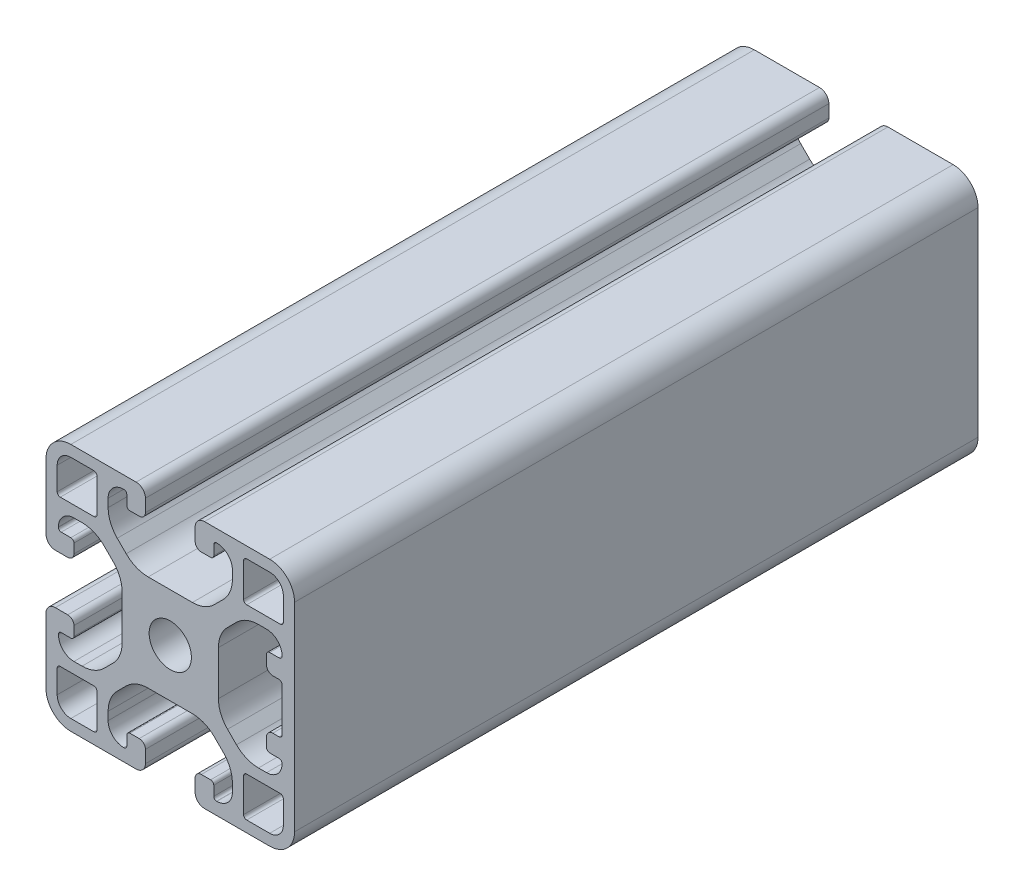
SolidWorks part; units mm, degrees
ref_plane "Piano frontale" through (0, 0, 0) normal (0, 0, 1) x (1, 0, 0)
ref_plane "Piano superiore" through (0, 0, 0) normal (0, 1, 0) x (1, 0, 0)
ref_plane "Piano destro" through (0, 0, 0) normal (1, 0, 0) x (0, 0, -1)
ref_plane "Piano1" through (0, 0, -340) normal (0, 0, -1) x (-1, 0, 0)
sketch "Schizzo1" plane through (0, 0, -340) normal (0, 0, -1) x (-1, 0, 0)
  line L0 (-12.3, -18.2) -> (-16, -18.2)
  line L1 (-18.2, -16) -> (-18.2, -12.3)
  line L2 (-17.7, -11.8) -> (-12.3, -11.8)
  line L3 (-11.8, -12.3) -> (-11.8, -17.7)
  line L4 (-11.8, 17.7) -> (-11.8, 12.3)
  line L5 (-12.3, 11.8) -> (-17.7, 11.8)
  line L6 (-18.2, 12.3) -> (-18.2, 16)
  line L7 (-16, 18.2) -> (-12.3, 18.2)
  line L8 (18.2, 16) -> (18.2, 12.3)
  line L9 (17.7, 11.8) -> (12.3, 11.8)
  line L10 (11.8, 12.3) -> (11.8, 17.7)
  line L11 (12.3, 18.2) -> (16, 18.2)
  line L12 (6.5, -15.5) -> (5, -15.5)
  line L13 (4, -16.5) -> (4, -18.5)
  line L14 (5.5, -20) -> (16, -20)
  line L15 (20, -16) -> (20, -5.5)
  line L16 (18.5, -4) -> (16.5, -4)
  line L17 (15.5, -5) -> (15.5, -6.5)
  line L18 (16, -7) -> (17.55, -7)
  line L19 (18, -7.45) -> (18, -7.5)
  line L20 (15.5, -10) -> (14.1924, -10)
  line L21 (10.6569, -8.5355) -> (9.2145, -7.0931)
  line L22 (7.75, -3.5576) -> (7.75, 3.5576)
  line L23 (9.2145, 7.0931) -> (10.6569, 8.5355)
  line L24 (14.1924, 10) -> (15.5, 10)
  line L25 (18, 7.5) -> (18, 7.45)
  line L26 (17.55, 7) -> (16, 7)
  line L27 (15.5, 6.5) -> (15.5, 5)
  line L28 (16.5, 4) -> (18.5, 4)
  line L29 (20, 5.5) -> (20, 16)
  line L30 (16, 20) -> (5.5, 20)
  line L31 (4, 18.5) -> (4, 16.5)
  line L32 (5, 15.5) -> (6.5, 15.5)
  line L33 (7, 16) -> (7, 17.55)
  line L34 (7.45, 18) -> (7.5, 18)
  line L35 (10, 15.5) -> (10, 14.1924)
  line L36 (8.5355, 10.6569) -> (7.0931, 9.2145)
  line L37 (3.5576, 7.75) -> (-3.5576, 7.75)
  line L38 (-7.0931, 9.2145) -> (-8.5355, 10.6569)
  line L39 (-10, 14.1924) -> (-10, 15.5)
  line L40 (-7.5, 18) -> (-7.45, 18)
  line L41 (-7, 17.55) -> (-7, 16)
  line L42 (-6.5, 15.5) -> (-5, 15.5)
  line L43 (-4, 16.5) -> (-4, 18.5)
  line L44 (-5.5, 20) -> (-16, 20)
  line L45 (-20, 16) -> (-20, -16)
  line L46 (-16, -20) -> (-5.5, -20)
  line L47 (-4, -18.5) -> (-4, -16.5)
  line L48 (-5, -15.5) -> (-6.5, -15.5)
  line L49 (-7, -16) -> (-7, -17.55)
  line L50 (-7.45, -18) -> (-7.5, -18)
  line L51 (-10, -15.5) -> (-10, -14.1924)
  line L52 (-8.5355, -10.6569) -> (-7.0931, -9.2145)
  line L53 (-3.5576, -7.75) -> (3.5576, -7.75)
  line L54 (7.0931, -9.2145) -> (8.5355, -10.6569)
  line L55 (10, -14.1924) -> (10, -15.5)
  line L56 (7.5, -18) -> (7.45, -18)
  line L57 (7, -17.55) -> (7, -16)
  line L58 (18.2, -12.3) -> (18.2, -16)
  line L59 (16, -18.2) -> (12.3, -18.2)
  line L60 (11.8, -17.7) -> (11.8, -12.3)
  line L61 (12.3, -11.8) -> (17.7, -11.8)
  line L62 (-16, 7) -> (-17.5, 7)
  line L63 (-15.5, 10) -> (-14.1924, 10)
  line L64 (-10.6569, 8.5355) -> (-9.2145, 7.0931)
  line L65 (-7.75, 3.5576) -> (-7.75, -3.5576)
  line L66 (-9.2145, -7.0931) -> (-10.6569, -8.5355)
  line L67 (-14.1924, -10) -> (-15.5, -10)
  line L68 (-17.5, -7) -> (-16, -7)
  line L69 (-15.5, -6.5) -> (-15.5, -5)
  line L70 (-16.5, -4) -> (-17.5, -4)
  line L71 (-18, -3.5) -> (-18, 3.5)
  line L72 (-17.5, 4) -> (-16.5, 4)
  line L73 (-15.5, 5) -> (-15.5, 6.5)
  arc A0 (-16, -18.2) -> (-18.2, -16) centre (-16, -16) cw
  arc A1 (-18.2, -12.3) -> (-17.7, -11.8) centre (-17.7, -12.3) cw
  arc A2 (-12.3, -11.8) -> (-11.8, -12.3) centre (-12.3, -12.3) cw
  arc A3 (-11.8, -17.7) -> (-12.3, -18.2) centre (-12.3, -17.7) cw
  arc A4 (-12.3, 18.2) -> (-11.8, 17.7) centre (-12.3, 17.7) cw
  arc A5 (-11.8, 12.3) -> (-12.3, 11.8) centre (-12.3, 12.3) cw
  arc A6 (-17.7, 11.8) -> (-18.2, 12.3) centre (-17.7, 12.3) cw
  arc A7 (-18.2, 16) -> (-16, 18.2) centre (-16, 16) cw
  arc A8 (16, 18.2) -> (18.2, 16) centre (16, 16) cw
  arc A9 (18.2, 12.3) -> (17.7, 11.8) centre (17.7, 12.3) cw
  arc A10 (12.3, 11.8) -> (11.8, 12.3) centre (12.3, 12.3) cw
  arc A11 (11.8, 17.7) -> (12.3, 18.2) centre (12.3, 17.7) cw
  arc A12 (5, -15.5) -> (4, -16.5) centre (5, -16.5) ccw
  arc A13 (4, -18.5) -> (5.5, -20) centre (5.5, -18.5) ccw
  arc A14 (16, -20) -> (20, -16) centre (16, -16) ccw
  arc A15 (20, -5.5) -> (18.5, -4) centre (18.5, -5.5) ccw
  arc A16 (16.5, -4) -> (15.5, -5) centre (16.5, -5) ccw
  arc A17 (15.5, -6.5) -> (16, -7) centre (16, -6.5) ccw
  arc A18 (17.55, -7) -> (18, -7.45) centre (17.55, -7.45) cw
  arc A19 (18, -7.5) -> (15.5, -10) centre (15.5, -7.5) cw
  arc A20 (14.1924, -10) -> (10.6569, -8.5355) centre (14.1924, -5) cw
  arc A21 (9.2145, -7.0931) -> (7.75, -3.5576) centre (12.75, -3.5576) cw
  arc A22 (7.75, 3.5576) -> (9.2145, 7.0931) centre (12.75, 3.5576) cw
  arc A23 (10.6569, 8.5355) -> (14.1924, 10) centre (14.1924, 5) cw
  arc A24 (15.5, 10) -> (18, 7.5) centre (15.5, 7.5) cw
  arc A25 (18, 7.45) -> (17.55, 7) centre (17.55, 7.45) cw
  arc A26 (16, 7) -> (15.5, 6.5) centre (16, 6.5) ccw
  arc A27 (15.5, 5) -> (16.5, 4) centre (16.5, 5) ccw
  arc A28 (18.5, 4) -> (20, 5.5) centre (18.5, 5.5) ccw
  arc A29 (20, 16) -> (16, 20) centre (16, 16) ccw
  arc A30 (5.5, 20) -> (4, 18.5) centre (5.5, 18.5) ccw
  arc A31 (4, 16.5) -> (5, 15.5) centre (5, 16.5) ccw
  arc A32 (6.5, 15.5) -> (7, 16) centre (6.5, 16) ccw
  arc A33 (7, 17.55) -> (7.45, 18) centre (7.45, 17.55) cw
  arc A34 (7.5, 18) -> (10, 15.5) centre (7.5, 15.5) cw
  arc A35 (10, 14.1924) -> (8.5355, 10.6569) centre (5, 14.1924) cw
  arc A36 (7.0931, 9.2145) -> (3.5576, 7.75) centre (3.5576, 12.75) cw
  arc A37 (-3.5576, 7.75) -> (-7.0931, 9.2145) centre (-3.5576, 12.75) cw
  arc A38 (-8.5355, 10.6569) -> (-10, 14.1924) centre (-5, 14.1924) cw
  arc A39 (-10, 15.5) -> (-7.5, 18) centre (-7.5, 15.5) cw
  arc A40 (-7.45, 18) -> (-7, 17.55) centre (-7.45, 17.55) cw
  arc A41 (-7, 16) -> (-6.5, 15.5) centre (-6.5, 16) ccw
  arc A42 (-5, 15.5) -> (-4, 16.5) centre (-5, 16.5) ccw
  arc A43 (-4, 18.5) -> (-5.5, 20) centre (-5.5, 18.5) ccw
  arc A44 (-16, 20) -> (-20, 16) centre (-16, 16) ccw
  arc A45 (-20, -16) -> (-16, -20) centre (-16, -16) ccw
  arc A46 (-5.5, -20) -> (-4, -18.5) centre (-5.5, -18.5) ccw
  arc A47 (-4, -16.5) -> (-5, -15.5) centre (-5, -16.5) ccw
  arc A48 (-6.5, -15.5) -> (-7, -16) centre (-6.5, -16) ccw
  arc A49 (-7, -17.55) -> (-7.45, -18) centre (-7.45, -17.55) cw
  arc A50 (-7.5, -18) -> (-10, -15.5) centre (-7.5, -15.5) cw
  arc A51 (-10, -14.1924) -> (-8.5355, -10.6569) centre (-5, -14.1924) cw
  arc A52 (-7.0931, -9.2145) -> (-3.5576, -7.75) centre (-3.5576, -12.75) cw
  arc A53 (3.5576, -7.75) -> (7.0931, -9.2145) centre (3.5576, -12.75) cw
  arc A54 (8.5355, -10.6569) -> (10, -14.1924) centre (5, -14.1924) cw
  arc A55 (10, -15.5) -> (7.5, -18) centre (7.5, -15.5) cw
  arc A56 (7.45, -18) -> (7, -17.55) centre (7.45, -17.55) cw
  arc A57 (7, -16) -> (6.5, -15.5) centre (6.5, -16) ccw
  arc A58 (17.7, -11.8) -> (18.2, -12.3) centre (17.7, -12.3) cw
  arc A59 (18.2, -16) -> (16, -18.2) centre (16, -16) cw
  arc A60 (12.3, -18.2) -> (11.8, -17.7) centre (12.3, -17.7) cw
  arc A61 (11.8, -12.3) -> (12.3, -11.8) centre (12.3, -12.3) cw
  circle A62 centre (0, 0) radius 3.4
  arc A63 (-15.5, 6.5) -> (-16, 7) centre (-16, 6.5) ccw
  arc A64 (-17.5, 7) -> (-18, 7.5) centre (-17.5, 7.5) cw
  arc A65 (-18, 7.5) -> (-15.5, 10) centre (-15.5, 7.5) cw
  arc A66 (-14.1924, 10) -> (-10.6569, 8.5355) centre (-14.1924, 5) cw
  arc A67 (-9.2145, 7.0931) -> (-7.75, 3.5576) centre (-12.75, 3.5576) cw
  arc A68 (-7.75, -3.5576) -> (-9.2145, -7.0931) centre (-12.75, -3.5576) cw
  arc A69 (-10.6569, -8.5355) -> (-14.1924, -10) centre (-14.1924, -5) cw
  arc A70 (-15.5, -10) -> (-18, -7.5) centre (-15.5, -7.5) cw
  arc A71 (-18, -7.5) -> (-17.5, -7) centre (-17.5, -7.5) cw
  arc A72 (-16, -7) -> (-15.5, -6.5) centre (-16, -6.5) ccw
  arc A73 (-15.5, -5) -> (-16.5, -4) centre (-16.5, -5) ccw
  arc A74 (-17.5, -4) -> (-18, -3.5) centre (-17.5, -3.5) cw
  arc A75 (-18, 3.5) -> (-17.5, 4) centre (-17.5, 3.5) cw
  arc A76 (-16.5, 4) -> (-15.5, 5) centre (-16.5, 5) ccw
extrude "Estrusione-Estrusione1" add sketch "Schizzo1" against normal blind 110
